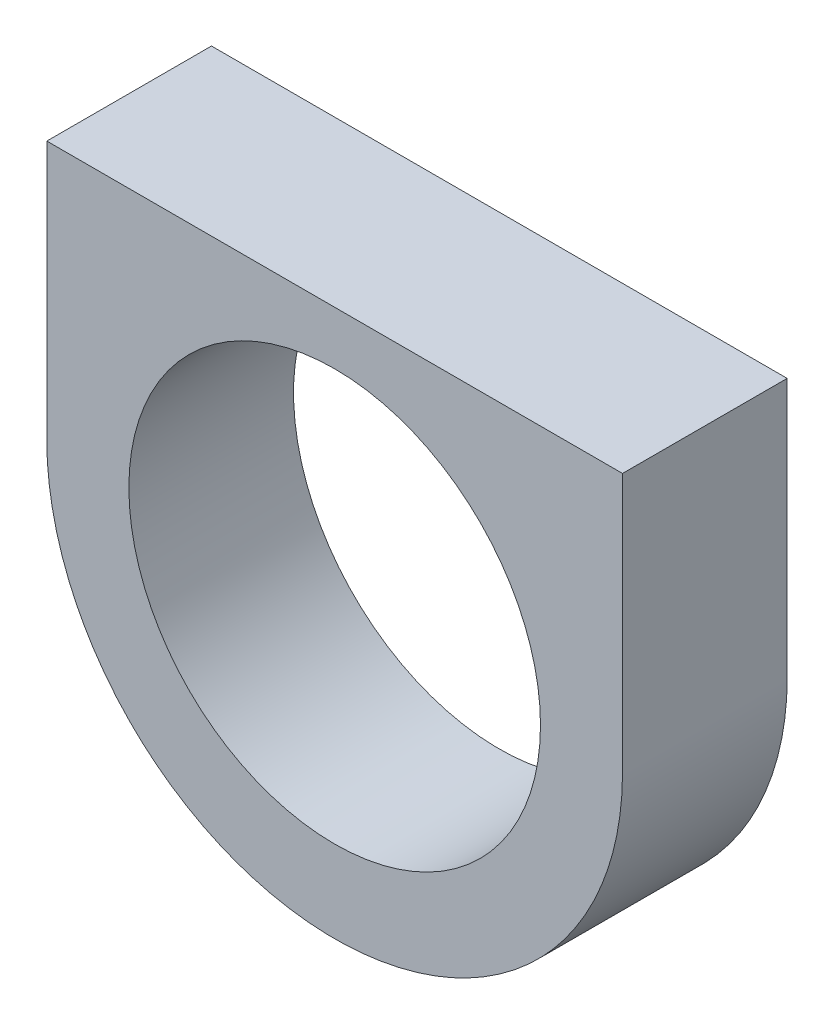
SolidWorks part; units mm, degrees
ref_plane "Front Plane" through (0, 0, 0) normal (0, 0, 1) x (1, 0, 0)
ref_plane "Top Plane" through (0, 0, 0) normal (0, 1, 0) x (1, 0, 0)
ref_plane "Right Plane" through (0, 0, 0) normal (1, 0, 0) x (0, 0, -1)
sketch "Sketch1" plane through (0, 0, 0) normal (0, 0, 1) x (1, 0, 0)
  line L0 (6.9931, 0) -> (-6.9931, 0)
  line L1 (-6.9931, 0) -> (-6.9931, -6.2948)
  line L2 (6.9931, 0) -> (6.9931, -6.2948)
  arc A0 (-6.9931, -6.2948) -> (6.9931, -6.2948) centre (0, -6.2948) ccw
  point P4 (0, 0)
  point P10 (0, 0)
sketch "Sketch2" plane through (0, 0, 0) normal (0, 0, 1) x (1, 0, 0)
  circle A0 centre (0, -6.2948) radius 5
ref_plane "Plane1" through (0, 0, 4) normal (0, 0, -1) x (-1, 0, 0)
sketch "Sketch3" plane through (0, 0, 4) normal (0, 0, -1) x (-1, 0, 0)
  line L0 (6.9931, 0) -> (-6.9931, 0)
  line L1 (-6.9931, 0) -> (-6.9931, -6.2948)
  line L2 (6.9931, 0) -> (6.9931, -6.2948)
  arc A0 (-6.9931, -6.2948) -> (6.9931, -6.2948) centre (0, -6.2948) ccw
  point P4 (0, 0)
  point P10 (0, 0)
loft "Loft1" add profiles "Sketch1", "Sketch3"
extrude "Cut-Extrude1" cut sketch "Sketch2" against normal through all both and the other way through all
